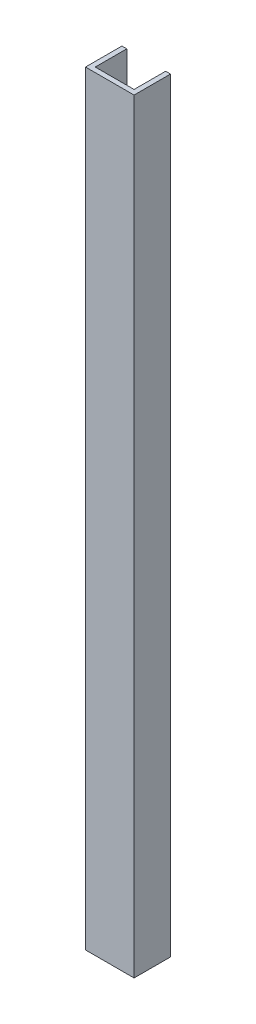
SolidWorks part; units mm, degrees
ref_plane "Спереди" through (0, 0, 0) normal (0, 0, 1) x (1, 0, 0)
ref_plane "Сверху" through (0, 0, 0) normal (0, 1, 0) x (1, 0, 0)
ref_plane "Справа" through (0, 0, 0) normal (1, 0, 0) x (0, 0, -1)
sketch "Эскиз1" plane through (0, 0, 0) normal (0, 1, 0) x (1, 0, 0)
  line L0 (-8, 0) -> (8, 0)
  line L1 (8, 0) -> (8, 13)
  line L2 (8, 13) -> (10, 13)
  line L3 (10, 13) -> (10, -2)
  line L4 (10, -2) -> (-10, -2)
  line L5 (0, 50.8491) -> (0, -43.6792) construction
  line L6 (-10, 13) -> (-10, -2)
  line L7 (-8, 13) -> (-10, 13)
  line L8 (-8, 0) -> (-8, 13)
  point P10 (0, -2)
  point P13 (0, 0)
  dimension "D1" = 20
  dimension "D2" = 15
  dimension "D3" = 2
  dimension "D4" = 2
extrude "Бобышка-Вытянуть1" add sketch "Эскиз1" along normal blind 315
